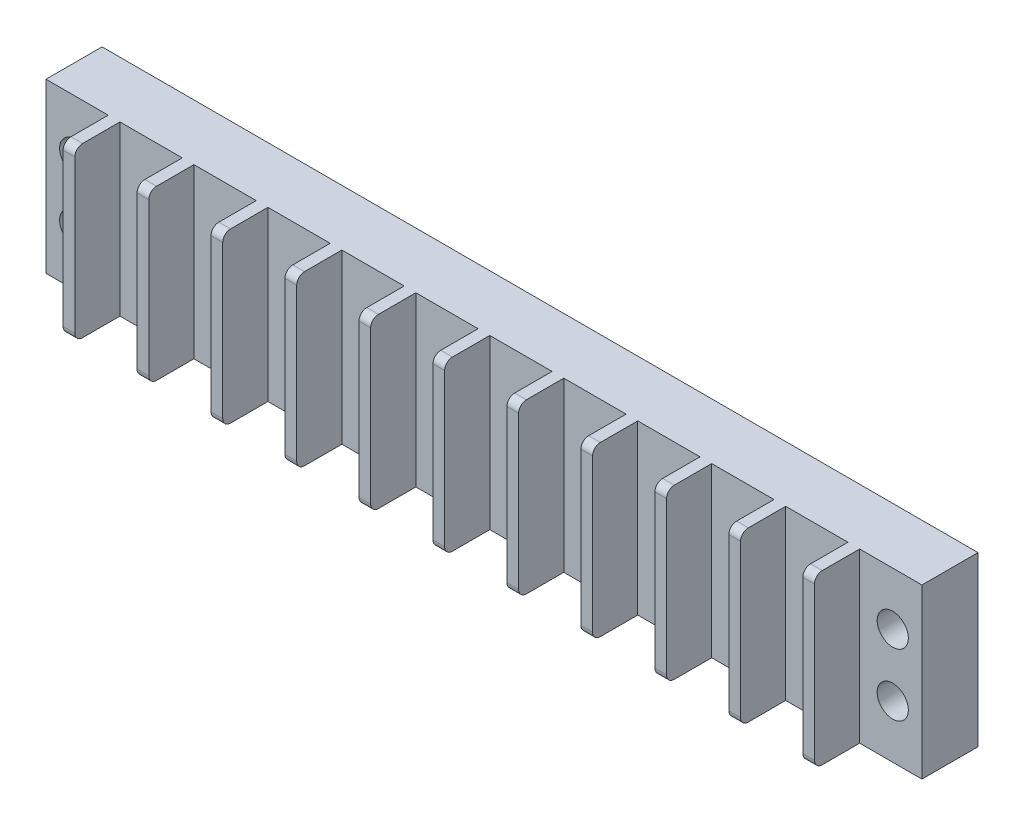
SolidWorks part; units mm, degrees
ref_plane "Front Plane" through (0, 0, 0) normal (0, 0, 1) x (1, 0, 0)
ref_plane "Top Plane" through (0, 0, 0) normal (0, 1, 0) x (1, 0, 0)
ref_plane "Right Plane" through (0, 0, 0) normal (1, 0, 0) x (0, 0, -1)
sketch "Sketch1" plane through (0, 0, 0) normal (0, 0, 1) x (1, 0, 0)
  line L0 (0, 10.8) -> (0, -10.8) construction
  line L1 (56.25, -10.8) -> (-56.25, -10.8)
  line L2 (56.25, -10.8) -> (56.25, 10.8)
  line L3 (56.25, 10.8) -> (-56.25, 10.8)
  line L4 (-56.25, -10.8) -> (-56.25, 10.8)
  line L5 (-56.25, 0) -> (56.25, 0) construction
  circle A0 centre (-52.5, 4) radius 2
  circle A1 centre (52.5, 4) radius 2
  circle A2 centre (52.5, -4) radius 2
  circle A3 centre (-52.5, -4) radius 2
  point P9 (0, 0)
  dimension "D3" = 4
  dimension "D1" = 112.5
  dimension "D2" = 21.6
  dimension "D4" = 105
  dimension "D5" = 8
extrude "Boss-Extrude1" add sketch "Sketch1" along normal blind 13
sketch "Sketch2" plane through (0, 0, 13) normal (0, 0, 1) x (1, 0, 0)
  line L0 (-46.75, 10.8) -> (-46.75, -10.8)
  line L2 (-56.25, -10.8) -> (56.25, -10.8) construction
  line L4 (-56.25, 10.8) -> (-48.25, 10.8)
  line L5 (-56.25, 10.8) -> (-56.25, -10.8)
  line L6 (-56.25, -10.8) -> (-48.25, -10.8)
  line L7 (-48.25, 10.8) -> (-48.25, -10.8)
  line L11 (-46.75, 10.8) -> (-38.75, 10.8)
  line L12 (-38.75, 10.8) -> (-38.75, -10.8)
  line L13 (-46.75, -10.8) -> (-38.75, -10.8)
  line L14 (-37.25, 10.8) -> (-37.25, -10.8)
  line L15 (-37.25, 10.8) -> (-29.25, 10.8)
  line L16 (-29.25, 10.8) -> (-29.25, -10.8)
  line L17 (-37.25, -10.8) -> (-29.25, -10.8)
  line L18 (-27.75, 10.8) -> (-27.75, -10.8)
  line L19 (-27.75, 10.8) -> (-19.75, 10.8)
  line L20 (-19.75, 10.8) -> (-19.75, -10.8)
  line L21 (-27.75, -10.8) -> (-19.75, -10.8)
  line L22 (-18.25, 10.8) -> (-18.25, -10.8)
  line L23 (-18.25, 10.8) -> (-10.25, 10.8)
  line L24 (-10.25, 10.8) -> (-10.25, -10.8)
  line L25 (-18.25, -10.8) -> (-10.25, -10.8)
  line L26 (-8.75, 10.8) -> (-8.75, -10.8)
  line L27 (-8.75, 10.8) -> (-0.75, 10.8)
  line L28 (-0.75, 10.8) -> (-0.75, -10.8)
  line L29 (-8.75, -10.8) -> (-0.75, -10.8)
  line L30 (0.75, 10.8) -> (0.75, -10.8)
  line L31 (0.75, 10.8) -> (8.75, 10.8)
  line L32 (8.75, 10.8) -> (8.75, -10.8)
  line L33 (0.75, -10.8) -> (8.75, -10.8)
  line L34 (10.25, 10.8) -> (10.25, -10.8)
  line L35 (10.25, 10.8) -> (18.25, 10.8)
  line L36 (18.25, 10.8) -> (18.25, -10.8)
  line L37 (10.25, -10.8) -> (18.25, -10.8)
  line L38 (19.75, 10.8) -> (19.75, -10.8)
  line L39 (19.75, 10.8) -> (27.75, 10.8)
  line L40 (27.75, 10.8) -> (27.75, -10.8)
  line L41 (19.75, -10.8) -> (27.75, -10.8)
  line L42 (29.25, 10.8) -> (29.25, -10.8)
  line L43 (29.25, 10.8) -> (37.25, 10.8)
  line L44 (37.25, 10.8) -> (37.25, -10.8)
  line L45 (29.25, -10.8) -> (37.25, -10.8)
  line L46 (38.75, 10.8) -> (38.75, -10.8)
  line L47 (38.75, 10.8) -> (46.75, 10.8)
  line L48 (46.75, 10.8) -> (46.75, -10.8)
  line L49 (38.75, -10.8) -> (46.75, -10.8)
  line L50 (48.25, 10.8) -> (48.25, -10.8)
  line L51 (48.25, 10.8) -> (56.25, 10.8)
  line L52 (56.25, 10.8) -> (56.25, -10.8)
  line L53 (48.25, -10.8) -> (56.25, -10.8)
  dimension "D1" = 8
  dimension "D3" = 1.5
  dimension "D2" = 12
extrude "Cut-Extrude1" cut sketch "Sketch2" against normal blind 5.8
fillet "Fillet1" radius 1 22 edges at (-47.5, 10.8, 13) (-38, 10.8, 13) (-28.5, 10.8, 13) (-19, 10.8, 13) (-9.5, 10.8, 13) (0, 10.8, 13) (9.5, 10.8, 13) (19, 10.8, 13) (28.5, 10.8, 13) (38, 10.8, 13) (47.5, 10.8, 13) (47.5, -10.8, 13) (38, -10.8, 13) (28.5, -10.8, 13) (19, -10.8, 13) (9.5, -10.8, 13) (0, -10.8, 13) (-9.5, -10.8, 13) (-19, -10.8, 13) (-28.5, -10.8, 13) (-38, -10.8, 13) (-47.5, -10.8, 13)
